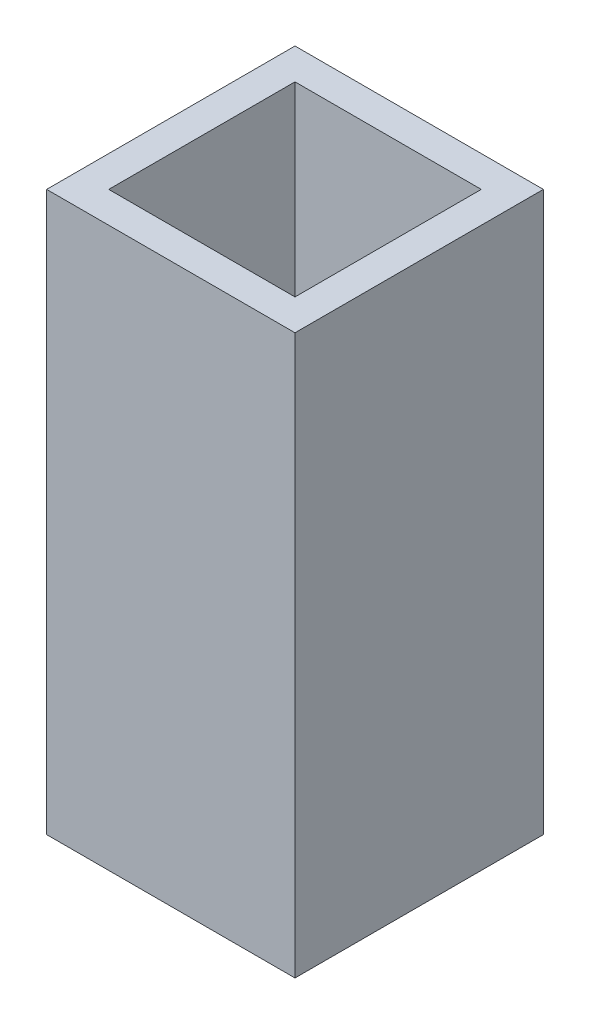
SolidWorks part; units mm, degrees
material "1060 Alloy"
ref_plane "Front Plane" through (0, 0, 0) normal (0, 0, 1) x (1, 0, 0)
ref_plane "Top Plane" through (0, 0, 0) normal (0, 1, 0) x (1, 0, 0)
ref_plane "Right Plane" through (0, 0, 0) normal (1, 0, 0) x (0, 0, -1)
sketch "Sketch1" plane through (0, 0, 0) normal (0, 1, 0) x (1, 0, 0)
  line L1 (-12.7, -12.7) -> (12.7, -12.7)
  line L2 (-12.7, -12.7) -> (-12.7, 12.7)
  line L3 (-12.7, 12.7) -> (12.7, 12.7)
  line L4 (12.7, -12.7) -> (12.7, 12.7)
  line L5 (-12.7, -12.7) -> (12.7, 12.7) construction
  line L6 (-12.7, 12.7) -> (12.7, -12.7) construction
  point P0 (0, 0)
  dimension "D1" = 25.4
extrude "Extrude-Thin1" add sketch "Sketch1" along normal blind 57.15 thin thin type one direction reverse wall 3.175
